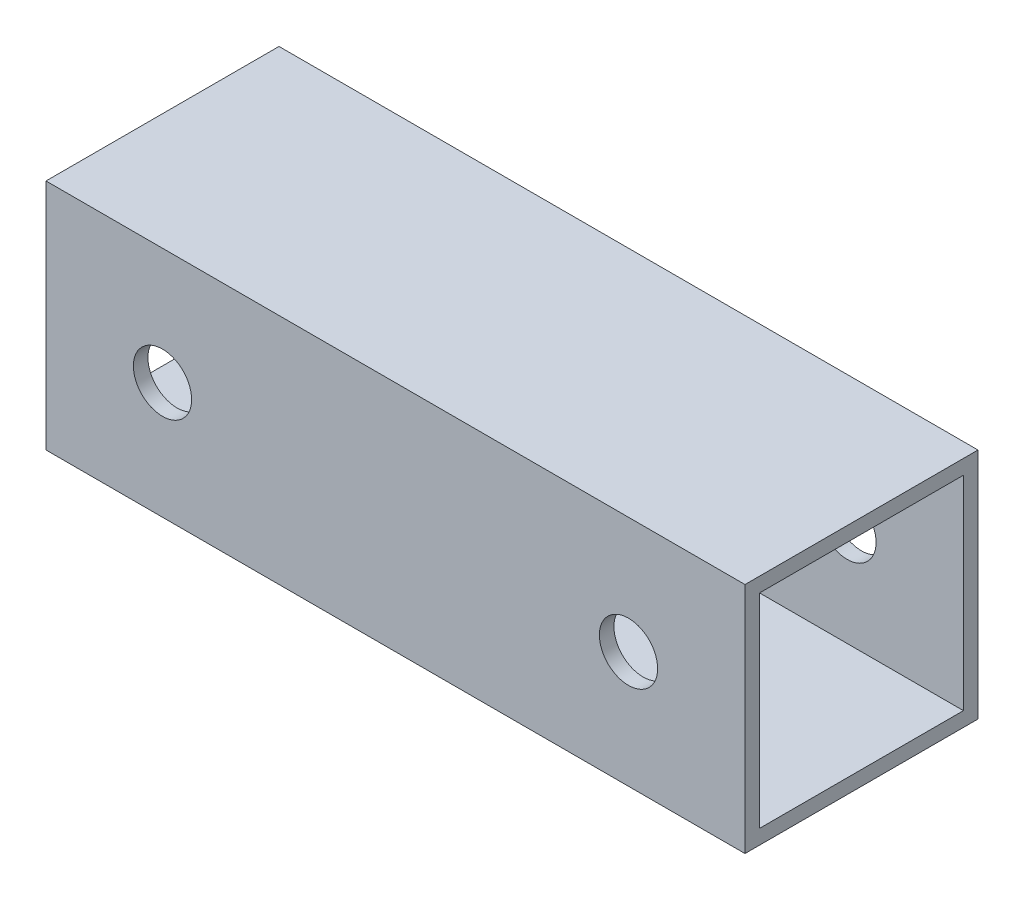
SolidWorks part; units mm, degrees
ref_plane "Front Plane" through (0, 0, 0) normal (0, 0, 1) x (1, 0, 0)
ref_plane "Top Plane" through (0, 0, 0) normal (0, 1, 0) x (1, 0, 0)
ref_plane "Right Plane" through (0, 0, 0) normal (1, 0, 0) x (0, 0, -1)
sketch "Sketch1" plane through (0, 0, 0) normal (1, 0, 0) x (0, 0, -1)
  line L1 (-12.7, 12.7) -> (12.7, 12.7)
  line L2 (-12.7, 12.7) -> (-12.7, -12.7)
  line L3 (-12.7, -12.7) -> (12.7, -12.7)
  line L4 (12.7, 12.7) -> (12.7, -12.7)
  line L5 (-12.7, 12.7) -> (12.7, -12.7) construction
  line L6 (-12.7, -12.7) -> (12.7, 12.7) construction
  line L7 (11.1125, -11.1125) -> (-11.1125, -11.1125)
  line L8 (11.1125, -11.1125) -> (11.1125, 11.1125)
  line L9 (11.1125, 11.1125) -> (-11.1125, 11.1125)
  line L10 (-11.1125, -11.1125) -> (-11.1125, 11.1125)
  line L11 (11.1125, -11.1125) -> (-11.1125, 11.1125) construction
  line L12 (11.1125, 11.1125) -> (-11.1125, -11.1125) construction
  point P0 (0, 0)
  point P6 (0, 0)
  dimension "D1" = 25.4
  dimension "D2" = 1.5875
extrude "Boss-Extrude1" add sketch "Sketch1" along normal blind 76.2
other "1in Square tube<1>"
sketch "Sketch2" plane through (0, 0, 12.7) normal (0, 0, 1) x (1, 0, 0)
  line L0 (0, 0) -> (12.7, 0) construction
  line L1 (0, 12.7) -> (0, -12.7) construction
  line L2 (12.7, 0) -> (63.5, 0) construction
  line L3 (63.5, 0) -> (76.2, 0) construction
  line L4 (76.2, 12.7) -> (76.2, -12.7) construction
  circle A0 centre (12.7, 0) radius 3.175
  circle A1 centre (63.5, 0) radius 3.175
  dimension "D1" = 6.35
  dimension "D2" = 12.7
extrude "Cut-Extrude1" cut sketch "Sketch2" against normal through all
